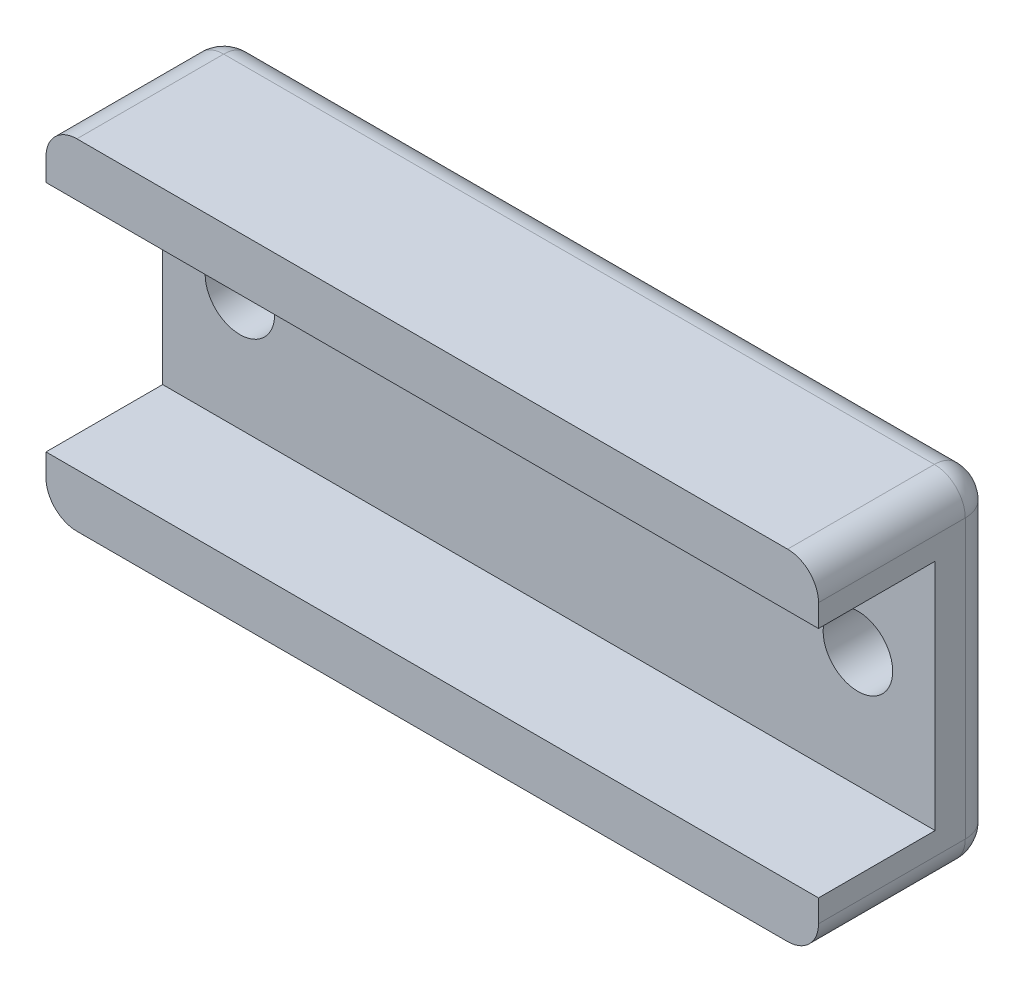
SolidWorks part; units mm, degrees
ref_plane "前视基准面" through (0, 0, 0) normal (0, 0, 1) x (1, 0, 0)
ref_plane "上视基准面" through (0, 0, 0) normal (0, 1, 0) x (1, 0, 0)
ref_plane "右视基准面" through (0, 0, 0) normal (1, 0, 0) x (0, 0, -1)
other "Configuration Table"
sketch "草图1" plane through (0, 0, 0) normal (0, 0, 1) x (1, 0, 0)
  line L1 (0, 0) -> (50, 0)
  line L2 (0, 0) -> (0, -22)
  line L3 (0, -22) -> (50, -22)
  line L4 (50, 0) -> (50, -22)
  dimension "D1" = 22
  dimension "D2" = 50
extrude "凸台-拉伸1" add sketch "草图1" along normal blind 23
sketch "草图2" plane through (50, 0, 0) normal (1, 0, 0) x (0, 0, -1)
  line L0 (-11.5, 0) -> (-11.5, -22) construction
  line L1 (-23, -11) -> (0, -11) construction
  line L3 (-19.05, -3.45) -> (-3.95, -3.45)
  line L4 (0, -22) -> (0, 0)
  line L5 (0, 0) -> (-23, 0)
  line L6 (-23, 0) -> (-23, -22)
  line L7 (-23, -22) -> (0, -22)
  line L8 (0, -22) -> (0, 0)
  line L9 (0, 0) -> (-23, 0)
  line L10 (-23, 0) -> (-23, -22)
  line L11 (-23, -22) -> (0, -22)
  line L12 (-19.05, -3.45) -> (-19.05, -18.55)
  line L13 (-19.05, -18.55) -> (-3.95, -18.55)
  line L14 (-3.95, -3.45) -> (-3.95, -18.55)
  dimension "D2" = 15.1
  dimension "D3" = 15.1
  dimension "D1" = 0
extrude "切除-拉伸1" cut sketch "草图2" against normal blind 77 contours L12 L3 L14 L13
sketch "草图3" plane through (0, 0, 0) normal (0, 0, -1) x (-1, 0, 0)
  line L0 (-50, -11) -> (-2.75, -11) construction
  line L1 (-25, 0) -> (-25, -22) construction
  line L2 (-50, 0) -> (0, 0) construction
  line L3 (0, -22) -> (-50, -22) construction
  line L4 (0, -3.45) -> (-50, -3.45)
  line L5 (-50, -3.45) -> (-50, -18.55)
  line L6 (-50, -18.55) -> (0, -18.55)
  line L7 (0, -18.55) -> (0, -3.45)
  line L8 (0, -3.45) -> (-50, -3.45)
  line L9 (-50, -3.45) -> (-50, -18.55)
  line L10 (-50, -18.55) -> (0, -18.55)
  line L17 (0, -18.55) -> (0, -3.45)
  circle A0 centre (-45, -11) radius 2.25
  circle A1 centre (-5, -11) radius 2.25
  dimension "D2" = 4.5
  dimension "D3" = 40
  dimension "D1" = 0
extrude "切除-拉伸2" cut sketch "草图3" against normal blind 49 contours A0 | A1
sketch "草图4" plane through (0, -22, 0) normal (0, -1, 0) x (1, 0, 0)
  line L0 (0, 11.5) -> (50, 11.5)
  line L4 (0, 0) -> (50, 0)
  line L5 (50, 0) -> (50, 23)
  line L6 (50, 23) -> (0, 23)
  line L7 (0, 23) -> (0, 0)
  line L8 (0, 0) -> (50, 0)
  line L9 (50, 0) -> (50, 23)
  line L10 (50, 23) -> (0, 23)
  line L11 (0, 23) -> (0, 0)
  line M7 (50, 0) -> (50, 23)
  line M8 (50, 23) -> (0, 23)
  line M9 (0, 23) -> (0, 0)
  dimension "D1" = 0
extrude "切除-拉伸3" cut sketch "草图4" against normal blind 49 contours L0 M9 M7 M8
fillet "圆角1" radius 2 2 edges at (25, 0, 0) (25, -22, 0)
fillet "圆角2" radius 2 10 edges at (50, -22, 6.75) (50, -21.4142, 0.5858) (50, -11, 0) (50, -0.5858, 0.5858) (0, -22, 6.75) (0, -21.4142, 0.5858) (0, -11, 0) (0, -0.5858, 0.5858) (50, 0, 6.75) (0, 0, 6.75)
